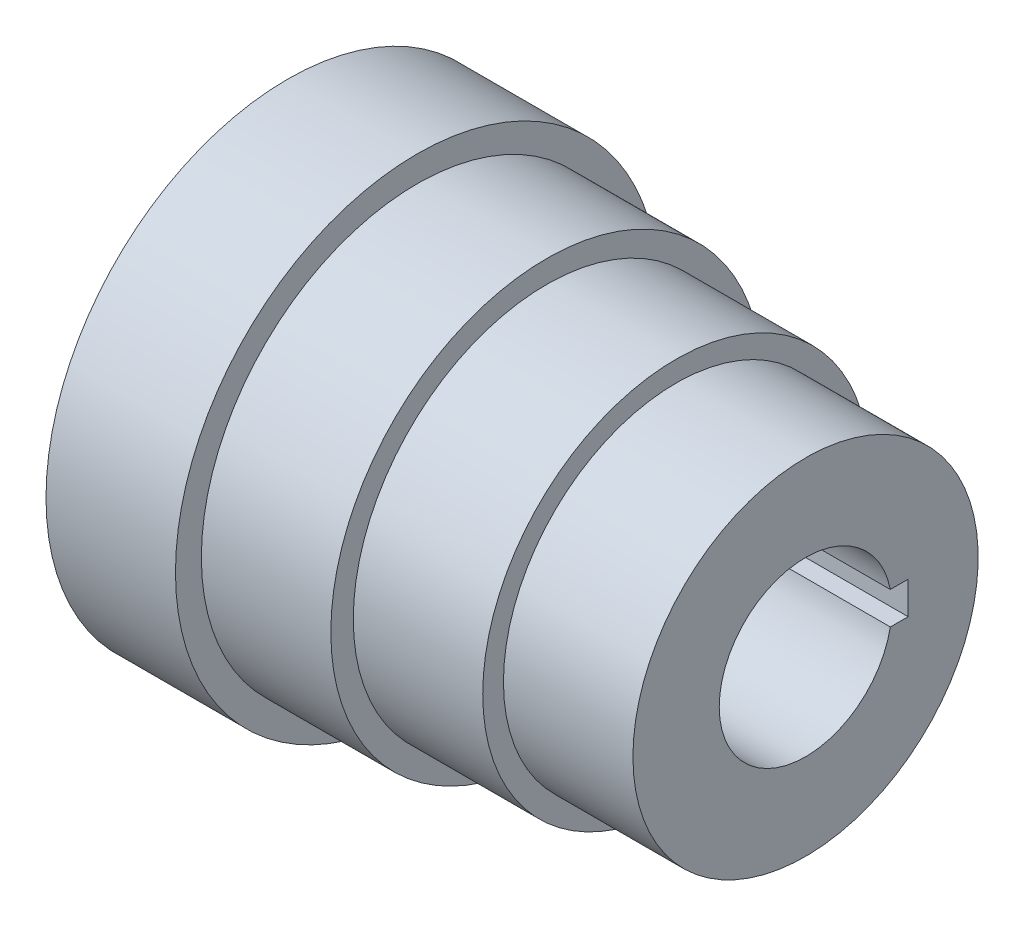
SolidWorks part; units mm, degrees
material "Alloy Steel"
ref_plane "Front Plane" through (0, 0, 0) normal (0, 0, 1) x (1, 0, 0)
ref_plane "Top Plane" through (0, 0, 0) normal (0, 1, 0) x (1, 0, 0)
ref_plane "Right Plane" through (0, 0, 0) normal (1, 0, 0) x (0, 0, -1)
sketch "Sketch1" plane through (0, 0, 0) normal (0, 0, 1) x (1, 0, 0)
  line L0 (-38.1, 0) -> (38.1, 0) construction
  line L1 (-38.1, 35.56) -> (-19.05, 35.56)
  line L2 (-19.05, 35.56) -> (-19.05, 31.75)
  line L3 (-19.05, 31.75) -> (0, 31.75)
  line L4 (0, 31.75) -> (0, 28.448)
  line L5 (0, 28.448) -> (19.05, 28.448)
  line L6 (19.05, 28.448) -> (19.05, 25.4)
  line L7 (19.05, 25.4) -> (38.1, 25.4)
  line L8 (38.1, 25.4) -> (38.1, 12.7)
  line L9 (38.1, 12.7) -> (-6.6124, 12.7)
  line L10 (-6.6124, 12.7) -> (-6.6124, 25.4) construction
  line L11 (-19.0964, 25.4) -> (-38.1, 25.4)
  line L12 (-38.1, 25.4) -> (-38.1, 35.56)
  line L13 (-19.05, 25.3973) -> (-19.0964, 25.4)
  arc A0 (-19.05, 25.3973) -> (-6.6124, 12.7) centre (-19.3124, 12.7) cw
  dimension "D13" = 19.05
  dimension "D14" = 19.05
  dimension "D2" = 12.7
  dimension "D3" = 19.05
  dimension "D4" = 19.05
  dimension "D5" = 19.05
  dimension "D6" = 25.4
  dimension "D7" = 71.12
  dimension "D8" = 19.05
  dimension "D9" = 63.5
  dimension "D10" = 56.896
  dimension "D11" = 50.8
  dimension "D12" = 50.8
revolve "Revolve1" add sketch "Sketch1" angle 360 about L0
sketch "Sketch3" plane through (38.1, 0, 0) normal (1, 0, 0) x (0, 0, -1)
  line L0 (0, 0) -> (12.7, 0) construction
  line L2 (10.3124, -2.3876) -> (15.0876, -2.3876)
  line L3 (10.3124, -2.3876) -> (10.3124, 2.3876)
  line L4 (10.3124, 2.3876) -> (15.0876, 2.3876)
  line L5 (15.0876, -2.3876) -> (15.0876, 2.3876)
  line L6 (10.3124, -2.3876) -> (15.0876, 2.3876) construction
  line L7 (10.3124, 2.3876) -> (15.0876, -2.3876) construction
  circle A0 centre (0, 0) radius 12.7 construction
  dimension "D1" = 4.7752
  dimension "D2" = 2.3876
extrude "Cut-Extrude1" cut sketch "Sketch3" against normal through all
